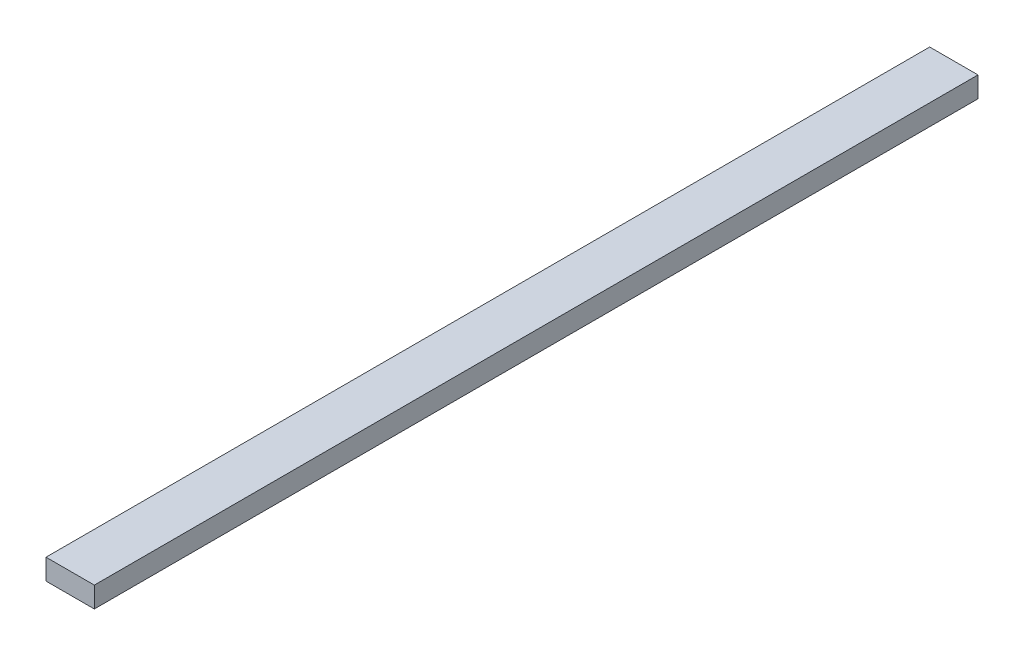
SolidWorks part; units mm, degrees
material "Pine"
ref_plane "Front Plane" through (0, 0, 0) normal (0, 0, 1) x (1, 0, 0)
ref_plane "Top Plane" through (0, 0, 0) normal (0, 1, 0) x (1, 0, 0)
ref_plane "Right Plane" through (0, 0, 0) normal (1, 0, 0) x (0, 0, -1)
sketch "Sketch1" plane through (0, 0, 0) normal (0, 0, 1) x (1, 0, 0)
  line L1 (0, 0) -> (88.9, 0)
  line L2 (0, 0) -> (0, -38.1)
  line L3 (0, -38.1) -> (88.9, -38.1)
  line L4 (88.9, 0) -> (88.9, -38.1)
  dimension "D1" = 88.9
  dimension "D2" = 38.1
extrude "Boss-Extrude1" add sketch "Sketch1" along normal blind 1625.6
equation "\"TableFrontWidth\"=64"
equation "\"TableSideWidth\"=28"
equation "\"LegWidth\"=3.5"
equation "\"LegHeight\"=32"
equation "\"LegDistToBottomStretcher\"=7"
equation "\"BottomStretcherLength\"=\"TableFrontWidth\""
equation "\"D1@Boss-Extrude1\"=\"TableFrontWidth\""
equation "\"SideStretcherLength\"=\"TableSideWidth\"-3"
equation "\"BottomSupportLength\"=\"TableSideWidth\"-3"
equation "\"BottomPlywoodFrontDim\"=\"TableFrontWidth\"-\"LegWidth\"*2-3"
equation "\"BottomPlywoodSideDim\"=\"BottomSupportLength\""
equation "\"TotalBottomSupports\"=4"
equation "\"TotalBottomSupportsLessOne\"=\"TotalBottomSupports\"-1"
equation "\"TotalTopSupports\"=5"
equation "\"TotalTopSupportsLessOne\"=\"TotalTopSupports\"-1"
equation "\"TopSupportSpread\"=\"TableFrontWidth\"-1.5"
equation "\"DistBetweenTopSupports\"=\"TopSupportSpread\"/\"TotalTopSupportsLessOne\""
equation "\"BottomSupportSpread\"= \"BottomPlywoodFrontDim\" - 1.5"
equation "\"DistBetweenBottomSupports\"=\"BottomSupportSpread\"/\"TotalBottomSupportsLessOne\""
equation "\"OverhangFrontDim\"=4"
equation "\"OverhangSideDim\"=4"
